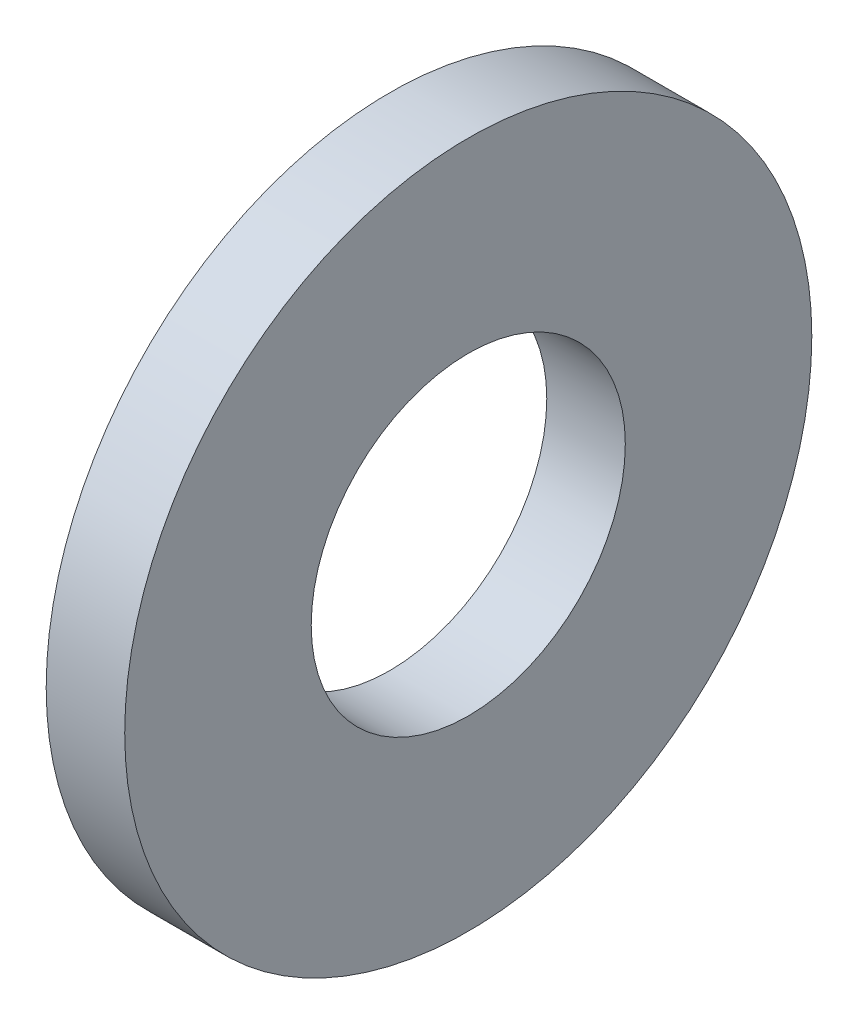
SolidWorks part; units mm, degrees
other "Preload Carriage Clamp Washer"
ref_plane "Front Plane" through (0, 0, 0) normal (0, 0, 1) x (1, 0, 0)
ref_plane "Top Plane" through (0, 0, 0) normal (0, 1, 0) x (1, 0, 0)
ref_plane "Right Plane" through (0, 0, 0) normal (1, 0, 0) x (0, 0, -1)
sketch3d "M3 washer outside sketch datum points"
  point P0 (53.9083, -19, -12)
  point P1 (53.9083, -9, -12)
  point P2 (53.9083, -19, -2)
ref_plane "M3 washer outside sketch plane" through (53.9083, 0, 0) normal (1, 0, 0) x (0, 0, -1)
sketch "M3 washer outside sketch" plane through (53.9083, 0, 0) normal (1, 0, 0) x (0, 0, -1)
  circle A0 centre (12, -19) radius 3.5
extrude "M3 washer outside" add sketch "M3 washer outside sketch" along normal blind 0.8 separate body
sketch3d "M3 washer bore sketch datum points"
  point P0 (53.8083, -19, -12)
  point P1 (53.8083, -9, -12)
  point P2 (53.8083, -19, -2)
ref_plane "M3 washer bore sketch plane" through (53.8083, 0, 0) normal (1, 0, 0) x (0, 0, -1)
sketch "M3 washer bore sketch" plane through (53.8083, 0, 0) normal (1, 0, 0) x (0, 0, -1)
  circle A0 centre (12, -19) radius 1.6
extrude "M3 washer bore" cut sketch "M3 washer bore sketch" along normal blind 1
